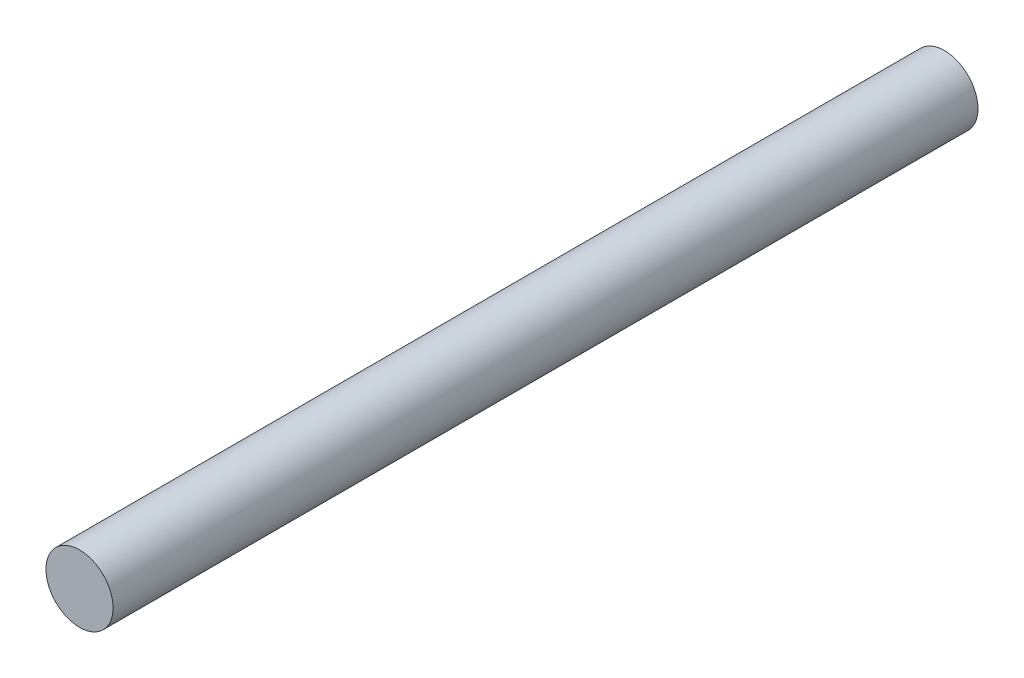
SolidWorks part; units mm, degrees
ref_plane "Front Plane" through (0, 0, 0) normal (0, 0, 1) x (1, 0, 0)
ref_plane "Top Plane" through (0, 0, 0) normal (0, 1, 0) x (1, 0, 0)
ref_plane "Right Plane" through (0, 0, 0) normal (1, 0, 0) x (0, 0, -1)
sketch "Sketch1" plane through (0, 0, 0) normal (0, 0, 1) x (1, 0, 0)
  circle A0 centre (0, 0) radius 4
  dimension "D1" = 8
extrude "Boss-Extrude1" add sketch "Sketch1" along normal blind 103
